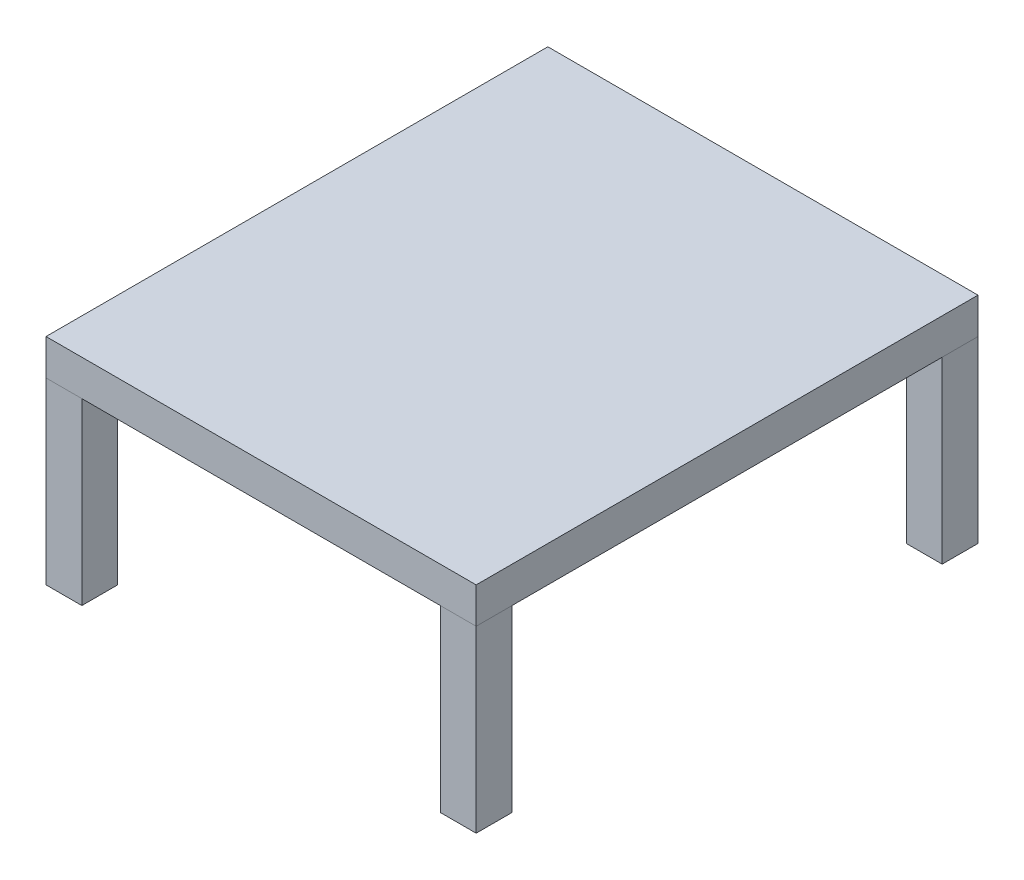
SolidWorks part; units mm, degrees
ref_plane "Front Plane" through (0, 0, 0) normal (0, 0, 1) x (1, 0, 0)
ref_plane "Top Plane" through (0, 0, 0) normal (0, 1, 0) x (1, 0, 0)
ref_plane "Right Plane" through (0, 0, 0) normal (1, 0, 0) x (0, 0, -1)
sketch "Sketch1" plane through (0, 0, 0) normal (0, 1, 0) x (1, 0, 0)
  line L0 (0, 630.2994) -> (0, 0) construction
  line L5 (-304.8, 355.6) -> (-254, 355.6)
  line L6 (-304.8, 355.6) -> (-304.8, 304.8)
  line L7 (-304.8, 304.8) -> (-254, 304.8)
  line L8 (-254, 355.6) -> (-254, 304.8)
  line L9 (-304.8, 355.6) -> (-254, 304.8) construction
  line L10 (-304.8, 304.8) -> (-254, 355.6) construction
  line L11 (0, 0) -> (-652.6893, 0) construction
  line L12 (-304.8, -355.6) -> (-304.8, -304.8)
  line L13 (-304.8, -304.8) -> (-254, -304.8)
  line L14 (-254, -355.6) -> (-254, -304.8)
  line L15 (-304.8, -355.6) -> (-254, -355.6)
  point P0 (-279.4, 330.2)
  dimension "D1" = 50.8
  dimension "D2" = 609.6
  dimension "D3" = 609.6
extrude "Boss-Extrude1" add sketch "Sketch1" along normal blind 254
mirror "Mirror2" about plane through (0, 0, 0) normal (1, 0, 0) of bodies 101 102
sketch "Sketch2" plane through (0, 254, 0) normal (0, 1, 0) x (1, 0, 0)
  line L1 (304.8, 355.6) -> (-304.8, 355.6)
  line L2 (304.8, 355.6) -> (304.8, -355.6)
  line L3 (304.8, -355.6) -> (-304.8, -355.6)
  line L4 (-304.8, 355.6) -> (-304.8, -355.6)
extrude "Boss-Extrude2" add sketch "Sketch2" along normal blind 50.8 separate body
other "Save Bodies1"
